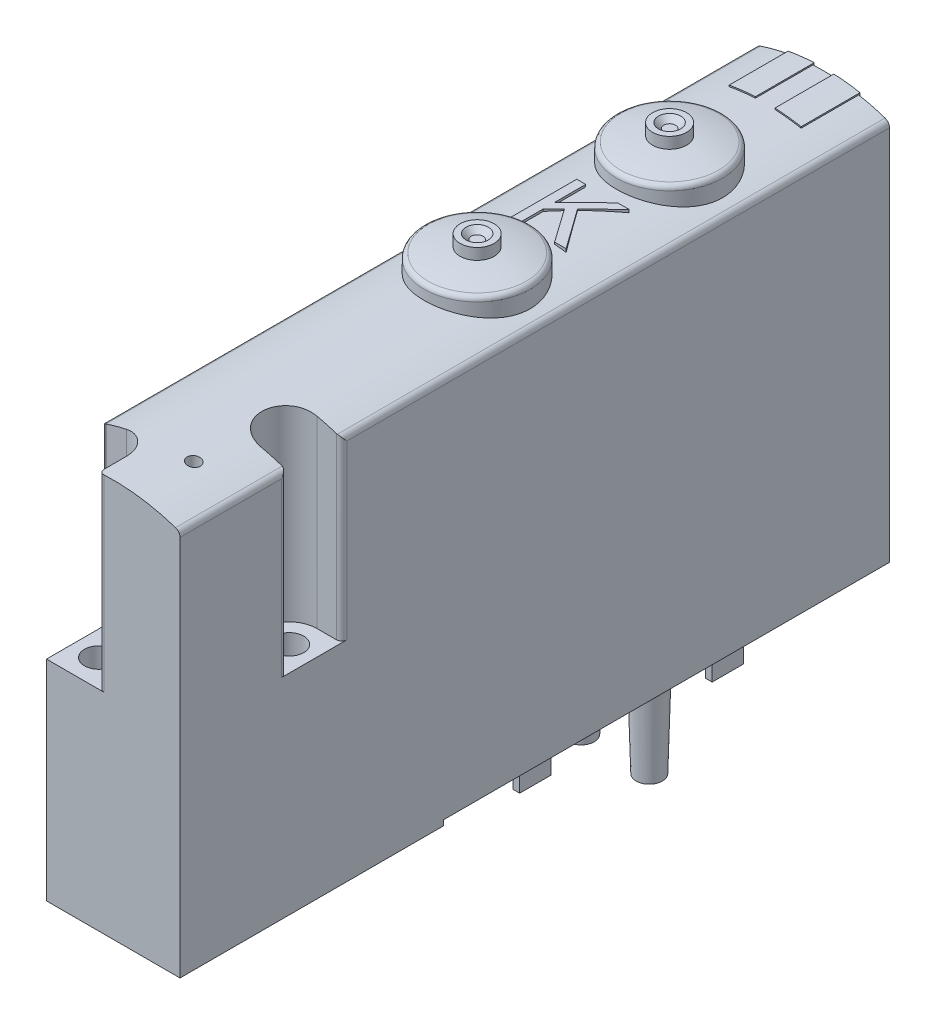
SolidWorks part; units mm, degrees
ref_plane "Front Plane" through (0, 0, 0) normal (0, 0, 1) x (1, 0, 0)
ref_plane "Top Plane" through (0, 0, 0) normal (0, 1, 0) x (1, 0, 0)
ref_plane "Right Plane" through (0, 0, 0) normal (1, 0, 0) x (0, 0, -1)
ref_plane "Plane1" through (0, 0, -23.2) normal (0, 0, 1) x (1, 0, 0)
sketch "Sketch1" plane through (0, 0, -23.2) normal (0, 0, 1) x (1, 0, 0)
  line L0 (-5.1, 29.151) -> (-5.1, 0)
  line L1 (-5.1, 0) -> (5.1, 0)
  line L2 (5.1, 0) -> (5.1, 29.151)
  arc A0 (5.1, 29.151) -> (4.7586, 29.6252) centre (4.6, 29.151) ccw
  arc A1 (4.7586, 29.6252) -> (-4.7586, 29.6252) centre (0, 15.4) ccw
  arc A2 (-4.7586, 29.6252) -> (-5.1, 29.151) centre (-4.6, 29.151) ccw
extrude "Boss-Extrude1" add sketch "Sketch1" along normal blind 54.2
ref_plane "Plane2" through (0, 29.4, 0) normal (0, 1, 0) x (1, 0, 0)
sketch "Sketch2" plane through (0, 29.4, 0) normal (0, 1, 0) x (1, 0, 0)
  line L0 (-2.0938, 1.5) -> (-1.4062, 1.5)
  line L1 (-1.4062, 1.5) -> (-1.4062, 3.25)
  line L2 (-1.4062, 3.25) -> (-0.5938, 4.0625)
  line L3 (-0.5938, 4.0625) -> (1.2188, 1.5)
  line L4 (1.2188, 1.5) -> (2.0938, 1.5)
  line L5 (2.0938, 1.5) -> (-0.0938, 4.5625)
  line L6 (-0.0938, 4.5625) -> (1.9062, 6.5)
  line L7 (1.9062, 6.5) -> (1.0312, 6.5)
  line L8 (1.0312, 6.5) -> (-1.4062, 4.125)
  line L9 (-1.4062, 4.125) -> (-1.4062, 6.5)
  line L10 (-1.4062, 6.5) -> (-2.0938, 6.5)
  line L11 (-2.0938, 6.5) -> (-2.0938, 1.5)
extrude "Boss-Extrude2" add sketch "Sketch2" along normal blind 1.1
ref_plane "Plane3" through (0, 30.4, 0) normal (0, 1, 0) x (1, 0, 0)
sketch "Sketch3" plane through (0, 30.4, 0) normal (0, 1, 0) x (1, 0, 0)
  circle A0 centre (3.2, -20.75) radius 1.1
extrude "Cut-Extrude1" cut sketch "Sketch3" against normal blind 31
ref_plane "Plane4" through (0, 30.4, 0) normal (0, 1, 0) x (1, 0, 0)
sketch "Sketch4" plane through (0, 30.4, 0) normal (0, 1, 0) x (1, 0, 0)
  line L0 (3.2, -22.85) -> (4.7, -22.85)
  line L1 (5.1, -23.25) -> (6.2, -23.25)
  line L2 (6.2, -23.25) -> (6.2, -18.25)
  line L3 (6.2, -18.25) -> (5.1, -18.25)
  line L4 (4.7, -18.65) -> (3.2, -18.65)
  arc A0 (3.2, -18.65) -> (3.2, -22.85) centre (3.2, -20.75) ccw
  arc A1 (4.7, -22.85) -> (5.1, -23.25) centre (4.7, -23.25) cw
  arc A2 (5.1, -18.25) -> (4.7, -18.65) centre (4.7, -18.25) cw
extrude "Cut-Extrude2" cut sketch "Sketch4" against normal blind 14.4
ref_plane "Plane5" through (0, 30.4, 0) normal (0, 1, 0) x (1, 0, 0)
sketch "Sketch5" plane through (0, 30.4, 0) normal (0, 1, 0) x (1, 0, 0)
  circle A0 centre (-3.2, -28.9) radius 1.1
extrude "Cut-Extrude3" cut sketch "Sketch5" against normal blind 31
ref_plane "Plane6" through (0, 30.4, 0) normal (0, 1, 0) x (1, 0, 0)
sketch "Sketch6" plane through (0, 30.4, 0) normal (0, 1, 0) x (1, 0, 0)
  line L0 (-6.2, -26.4) -> (-6.2, -31.9)
  line L1 (-6.2, -31.9) -> (-0.7, -31.9)
  line L2 (-0.7, -31.9) -> (-0.7, -31)
  line L3 (-1.1, -30.6) -> (-1.1, -28.9)
  line L4 (-3.2, -26.8) -> (-4.7, -26.8)
  line L5 (-5.1, -26.4) -> (-6.2, -26.4)
  arc A0 (-0.7, -31) -> (-1.1, -30.6) centre (-0.7, -30.6) cw
  arc A1 (-1.1, -28.9) -> (-3.2, -26.8) centre (-3.2, -28.9) ccw
  arc A2 (-4.7, -26.8) -> (-5.1, -26.4) centre (-4.7, -26.4) cw
extrude "Cut-Extrude4" cut sketch "Sketch6" against normal blind 14.4
ref_plane "Plane7" through (0, 0, 0) normal (1, 0, 0) x (0, 0, -1)
sketch "Sketch7" plane through (0, 0, 0) normal (1, 0, 0) x (0, 0, -1)
  line L0 (-10.88, 0.4) -> (-10.88, 0)
  line L1 (-10.88, 0) -> (23.22, 0)
  line L2 (23.22, 0) -> (23.22, 0.4)
  line L3 (23.22, 0.4) -> (-10.88, 0.4)
extrude "Cut-Extrude5" cut sketch "Sketch7" against normal blind 6 and the other way blind 6
ref_plane "Plane8" through (0, 0, 0) normal (0, 1, 0) x (1, 0, 0)
sketch "Sketch8" plane through (0, 0, 0) normal (0, 1, 0) x (1, 0, 0)
  line L0 (-3.15, 2.4653) -> (-3.15, -2.4653)
  line L1 (3.15, -2.4653) -> (3.15, 2.4653)
  arc A0 (-3.15, -2.4653) -> (3.15, -2.4653) centre (0, 0) ccw
  arc A1 (3.15, 2.4653) -> (-3.15, 2.4653) centre (0, 0) ccw
extrude "Cut-Extrude6" cut sketch "Sketch8" along normal blind 1.9
ref_plane "Plane9" through (0, 0, 0) normal (0, 1, 0) x (1, 0, 0)
sketch "Sketch9" plane through (0, 0, 0) normal (0, 1, 0) x (1, 0, 0)
  line L0 (-3.15, 17.1653) -> (-3.15, 12.2347)
  line L1 (3.15, 12.2347) -> (3.15, 17.1653)
  arc A0 (-3.15, 12.2347) -> (3.15, 12.2347) centre (0, 14.7) ccw
  arc A1 (3.15, 17.1653) -> (-3.15, 17.1653) centre (0, 14.7) ccw
extrude "Cut-Extrude7" cut sketch "Sketch9" along normal blind 1.9
ref_plane "Plane10" through (0, 0, 0) normal (1, 0, 0) x (0, 0, -1)
sketch "Sketch10" plane through (0, 0, 0) normal (1, 0, 0) x (0, 0, -1)
  line L0 (0, 2.1) -> (3.05, 2.1)
  line L1 (3.05, 2.1) -> (3.05, 1.1)
  line L2 (3.05, 1.1) -> (2.25, 1.1)
  line L3 (2.25, 1.1) -> (2.25, -1.4)
  line L4 (2.25, -1.4) -> (2.65, -1.4)
  line L5 (2.65, -1.4) -> (2.65, -1.72)
  line L6 (2.65, -1.72) -> (2.4306, -2.1)
  line L7 (2.4306, -2.1) -> (0, -2.1)
  line L8 (0, -2.1) -> (0, 2.1)
  line L9 (0, -2.1) -> (0, 2.1) construction
revolve "Revolve1" add sketch "Sketch10" angle 360 about L9
ref_plane "Plane11" through (0, 0, 0) normal (1, 0, 0) x (0, 0, -1)
sketch "Sketch11" plane through (0, 0, 0) normal (1, 0, 0) x (0, 0, -1)
  line L0 (14.7, 2.1) -> (17.75, 2.1)
  line L1 (17.75, 2.1) -> (17.75, 1.1)
  line L2 (17.75, 1.1) -> (16.95, 1.1)
  line L3 (16.95, 1.1) -> (16.95, -1.4)
  line L4 (16.95, -1.4) -> (17.35, -1.4)
  line L5 (17.35, -1.4) -> (17.35, -1.72)
  line L6 (17.35, -1.72) -> (17.1306, -2.1)
  line L7 (17.1306, -2.1) -> (14.7, -2.1)
  line L8 (14.7, -2.1) -> (14.7, 2.1)
  line L9 (14.7, -2.1) -> (14.7, 2.1) construction
revolve "Revolve2" add sketch "Sketch11" angle 360 about L9
ref_plane "Plane12" through (0, 0, -7.35) normal (0, 0, 1) x (1, 0, 0)
sketch "Sketch12" plane through (0, 0, -7.35) normal (0, 0, 1) x (1, 0, 0)
  line L0 (2.6, 0.4) -> (3.8, 0.4)
  line L1 (3.8, 0.4) -> (3.6, -6.9)
  line L2 (2.6, -7.0623) -> (2.6, 0.4)
  line L3 (2.6, -7.0623) -> (2.6, 0.4) construction
  arc A0 (3.6, -6.9) -> (2.6, -7.0623) centre (2.6, -3.9) cw
revolve "Revolve3" add sketch "Sketch12" angle 360 about L3
ref_plane "Plane13" through (0, 0, -7.35) normal (0, 0, 1) x (1, 0, 0)
sketch "Sketch13" plane through (0, 0, -7.35) normal (0, 0, 1) x (1, 0, 0)
  line L0 (-2.6, 0.4) -> (-1.4, 0.4)
  line L1 (-1.4, 0.4) -> (-1.6, -6.9)
  line L2 (-2.6, -7.0623) -> (-2.6, 0.4)
  line L3 (-2.6, -7.0623) -> (-2.6, 0.4) construction
  arc A0 (-1.6, -6.9) -> (-2.6, -7.0623) centre (-2.6, -3.9) cw
revolve "Revolve4" add sketch "Sketch13" angle 360 about L3
ref_plane "Plane14" through (0, -2.1, 0) normal (0, -1, 0) x (-1, 0, 0)
sketch "Sketch14" plane through (0, -2.1, 0) normal (0, -1, 0) x (-1, 0, 0)
  line L0 (-1.25, -1.2) -> (-0.75, -1.2)
  line L1 (-0.75, -1.2) -> (-0.75, 1.2)
  line L2 (-0.75, 1.2) -> (-1.25, 1.2)
  line L3 (-1.25, 1.2) -> (-1.25, -1.2)
extrude "Boss-Extrude3" add sketch "Sketch14" along normal blind 2.5
ref_plane "Plane15" through (0, -2.1, 0) normal (0, -1, 0) x (-1, 0, 0)
sketch "Sketch15" plane through (0, -2.1, 0) normal (0, -1, 0) x (-1, 0, 0)
  line L0 (0.75, -1.2) -> (1.25, -1.2)
  line L1 (1.25, -1.2) -> (1.25, 1.2)
  line L2 (1.25, 1.2) -> (0.75, 1.2)
  line L3 (0.75, 1.2) -> (0.75, -1.2)
extrude "Boss-Extrude4" add sketch "Sketch15" along normal blind 2.5
ref_plane "Plane16" through (0, -2.1, 0) normal (0, -1, 0) x (-1, 0, 0)
sketch "Sketch16" plane through (0, -2.1, 0) normal (0, -1, 0) x (-1, 0, 0)
  line L0 (-1.25, 13.5) -> (-0.75, 13.5)
  line L1 (-0.75, 13.5) -> (-0.75, 15.9)
  line L2 (-0.75, 15.9) -> (-1.25, 15.9)
  line L3 (-1.25, 15.9) -> (-1.25, 13.5)
extrude "Boss-Extrude5" add sketch "Sketch16" along normal blind 2.5
ref_plane "Plane17" through (0, -2.1, 0) normal (0, -1, 0) x (-1, 0, 0)
sketch "Sketch17" plane through (0, -2.1, 0) normal (0, -1, 0) x (-1, 0, 0)
  line L0 (0.75, 13.5) -> (1.25, 13.5)
  line L1 (1.25, 13.5) -> (1.25, 15.9)
  line L2 (1.25, 15.9) -> (0.75, 15.9)
  line L3 (0.75, 15.9) -> (0.75, 13.5)
extrude "Boss-Extrude6" add sketch "Sketch17" along normal blind 2.5
ref_plane "Plane18" through (0, 0, 0) normal (1, 0, 0) x (0, 0, -1)
sketch "Sketch18" plane through (0, 0, 0) normal (1, 0, 0) x (0, 0, -1)
  line L0 (-3.2, 32.4) -> (-2.75, 32.4)
  line L1 (-2.75, 32.4) -> (-2.35, 32.8)
  line L2 (-2.35, 32.8) -> (-1.9, 32.8)
  line L3 (-1.9, 32.8) -> (-1.9, 31.9436)
  line L4 (0.85, 31.1364) -> (0.85, 28.1)
  line L5 (0.85, 28.1) -> (-3.2, 28.1)
  line L6 (-3.2, 28.1) -> (-3.2, 32.4)
  line L7 (-3.2, 28.1) -> (-3.2, 32.8) construction
  arc A0 (-1.9, 31.9436) -> (0.55, 31.5237) centre (-3.2, 17) cw
  arc A1 (0.55, 31.5237) -> (0.85, 31.1364) centre (0.45, 31.1364) cw
revolve "Revolve5" add sketch "Sketch18" angle 360 about L7
ref_plane "Plane19" through (0, 0, 0) normal (1, 0, 0) x (0, 0, -1)
sketch "Sketch19" plane through (0, 0, 0) normal (1, 0, 0) x (0, 0, -1)
  line L0 (11.5, 32.4) -> (11.95, 32.4)
  line L1 (11.95, 32.4) -> (12.35, 32.8)
  line L2 (12.35, 32.8) -> (12.8, 32.8)
  line L3 (12.8, 32.8) -> (12.8, 31.9436)
  line L4 (15.55, 31.1364) -> (15.55, 28.1)
  line L5 (15.55, 28.1) -> (11.5, 28.1)
  line L6 (11.5, 28.1) -> (11.5, 32.4)
  line L7 (11.5, 28.1) -> (11.5, 32.8) construction
  arc A0 (12.8, 31.9436) -> (15.25, 31.5237) centre (11.5, 17) cw
  arc A1 (15.25, 31.5237) -> (15.55, 31.1364) centre (15.15, 31.1364) cw
revolve "Revolve6" add sketch "Sketch19" angle 360 about L7
ref_plane "Plane20" through (0, 0, 26.6) normal (0, 0, 1) x (1, 0, 0)
sketch "Sketch20" plane through (0, 0, 26.6) normal (0, 0, 1) x (1, 0, 0)
  line L0 (1.75, 30.5) -> (2.25, 30.5)
  line L1 (2.25, 30.5) -> (2.25, 25.3)
  line L2 (2.25, 25.3) -> (1.75, 25.0113)
  line L3 (1.75, 25.0113) -> (1.75, 30.5)
  line L4 (1.75, 25.0113) -> (1.75, 30.5) construction
revolve "Cut-Revolve1" cut sketch "Sketch20" angle 360 about L4
ref_plane "Plane21" through (0, 0, -23.3) normal (0, 0, 1) x (1, 0, 0)
sketch "Sketch21" plane through (0, 0, -23.3) normal (0, 0, 1) x (1, 0, 0)
  line L0 (0.75, 30.4814) -> (0.75, 27)
  line L1 (0.75, 27) -> (2.75, 27)
  line L2 (2.75, 27) -> (2.75, 30.2475)
  arc A0 (2.75, 30.2475) -> (0.75, 30.4814) centre (0, 15.4) ccw
extrude "Boss-Extrude7" add sketch "Sketch21" along normal blind 4.5
ref_plane "Plane22" through (0, 0, -23.3) normal (0, 0, 1) x (1, 0, 0)
sketch "Sketch22" plane through (0, 0, -23.3) normal (0, 0, 1) x (1, 0, 0)
  line L0 (-2.75, 30.2475) -> (-2.75, 27)
  line L1 (-2.75, 27) -> (-0.75, 27)
  line L2 (-0.75, 27) -> (-0.75, 30.4814)
  arc A0 (-0.75, 30.4814) -> (-2.75, 30.2475) centre (0, 15.4) ccw
extrude "Boss-Extrude8" add sketch "Sketch22" along normal blind 4.5
